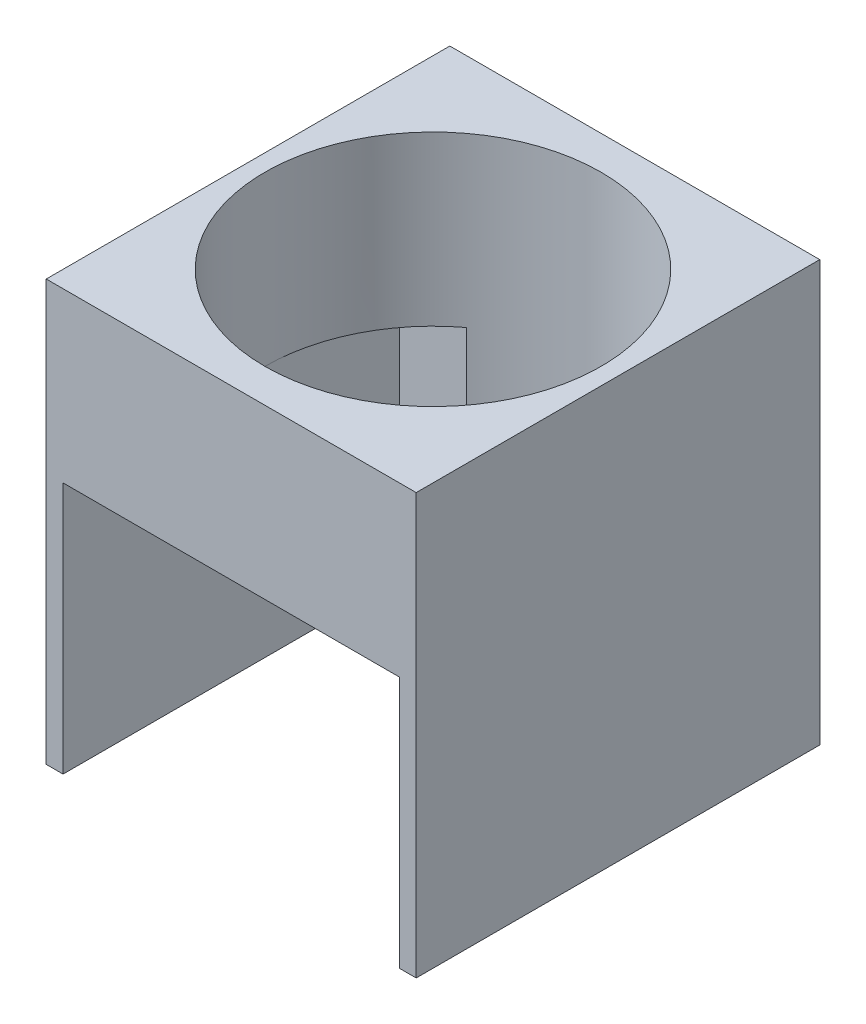
SolidWorks part; units mm, degrees
ref_plane "정면" through (0, 0, 0) normal (0, 0, 1) x (1, 0, 0)
ref_plane "윗면" through (0, 0, 0) normal (0, 1, 0) x (1, 0, 0)
ref_plane "우측면" through (0, 0, 0) normal (1, 0, 0) x (0, 0, -1)
sketch "Sketch1" plane through (0, 0, 0) normal (0, 1, 0) x (1, 0, 0)
  line L1 (0, 0) -> (670, 0)
  line L2 (0, 0) -> (0, 120)
  line L3 (0, 120) -> (670, 120)
  line L4 (670, 0) -> (670, 120)
  dimension "700" = 670
  dimension "D2" = 120
extrude "Boss-Extrude1" add sketch "Sketch1" along normal blind 530
sketch "Sketch2" plane through (0, 0, 0) normal (0, 0, 1) x (1, 0, 0)
  line L0 (0, 530) -> (0, 0) construction
  line L1 (10, 280) -> (110, 280)
  line L2 (10, 280) -> (10, 480)
  line L3 (10, 480) -> (110, 480)
  line L4 (110, 280) -> (110, 480)
  line L5 (0, 0) -> (670, 0) construction
  line L6 (120, 280) -> (120, 480)
  line L7 (120, 280) -> (220, 280)
  line L8 (220, 280) -> (220, 480)
  line L9 (120, 480) -> (220, 480)
  line L10 (230, 280) -> (230, 480)
  line L11 (230, 280) -> (330, 280)
  line L12 (330, 280) -> (330, 480)
  line L13 (230, 480) -> (330, 480)
  line L14 (340, 280) -> (340, 480)
  line L15 (340, 280) -> (440, 280)
  line L16 (440, 280) -> (440, 480)
  line L17 (340, 480) -> (440, 480)
  line L18 (450, 280) -> (450, 480)
  line L19 (450, 280) -> (550, 280)
  line L20 (550, 280) -> (550, 480)
  line L21 (450, 480) -> (550, 480)
  line L22 (560, 280) -> (560, 480)
  line L23 (560, 280) -> (660, 280)
  line L24 (660, 280) -> (660, 480)
  line L25 (560, 480) -> (660, 480)
  line L27 (10, 10) -> (660, 10)
  line L28 (10, 10) -> (10, 260)
  line L29 (10, 260) -> (660, 260)
  line L30 (660, 10) -> (660, 260)
  line L31 (0, 530) -> (670, 530) construction
  point P6 (10, 380)
  dimension "D1" = 100
  dimension "D2" = 200
  dimension "D3" = 10
  dimension "D4" = 50
  dimension "D6" = 10
  dimension "D7" = 20
  dimension "D5" = 6
extrude "Cut-Extrude1" cut sketch "Sketch2" against normal blind 100
sketch "Sketch3" plane through (0, 530, 0) normal (0, 1, 0) x (1, 0, 0)
  line L1 (670, 120) -> (0, 120) construction
  line L2 (0, 120) -> (0, 0) construction
  circle A0 centre (60, 60) radius 50
  circle A1 centre (170, 60) radius 50
  circle A2 centre (280, 60) radius 50
  circle A3 centre (390, 60) radius 50
  circle A4 centre (500, 60) radius 50
  circle A5 centre (610, 60) radius 50
  dimension "D1" = 100
  dimension "D2" = 10
  dimension "D3" = 10
  dimension "D4" = 6
extrude "Cut-Extrude2" cut sketch "Sketch3" against normal blind 260
hole_wizard "Ø12.0 (12) Diameter Hole2" positions "3DSketch1" profile "Sketch7" hole size "Ø12.0" standard "Ansi Metric"
sketch3d "3DSketch1"
  point P0 (59.7046, 270, -102.4117)
  point P2 (171.5567, 270, -102.6076)
  point P4 (280.8723, 270, -102.3969)
  point P6 (391.0687, 270, -102.7535)
  point P8 (500.7133, 270, -101.754)
  point P10 (609.5165, 270, -101.1227)
sketch "Sketch7" plane through (59.7046, 270, -102.4117) normal (1, 0, 0) x (0, 0, 1)
  line L0 (0, 0) -> (0, 33.6052)
  line L1 (0, 33.6052) -> (6, 30)
  line L2 (6, 30) -> (6, 0)
  line L5 (6, 0) -> (0, 0)
  line L10 (0, 33.6052) -> (-6, 30) construction
  line L11 (0, -6.35) -> (0, 107.95) construction
  dimension "구멍 지름" = 12
  dimension "구멍 깊이" = 30
  dimension "드릴 각도" = 118
sketch "Sketch8" plane through (0, 0, 0) normal (0, 0, 1) x (1, 0, 0)
  line L0 (660, 280) -> (660, 480) construction
  line L1 (10, 280) -> (660, 280)
  line L2 (10, 280) -> (10, 330)
  line L3 (10, 330) -> (660, 330)
  line L4 (660, 280) -> (660, 330)
  dimension "D1" = 50
extrude "Boss-Extrude2" add sketch "Sketch8" against normal blind 5
sketch "Sketch9" plane through (670, 0, 0) normal (1, 0, 0) x (0, 0, -1)
  line L0 (0, 530) -> (0, 0) construction
  line L1 (10, 10) -> (20, 10)
  line L2 (10, 10) -> (10, 260)
  line L3 (10, 260) -> (20, 260)
  line L4 (20, 10) -> (20, 260)
  line L5 (0, 0) -> (120, 0) construction
  dimension "D1" = 10
  dimension "D2" = 10
  dimension "D3" = 10
  dimension "D4" = 250
extrude "Cut-Extrude3" cut sketch "Sketch9" against normal blind 717
sketch "Sketch10" plane through (0, 10, 0) normal (0, 1, 0) x (1, 0, 0)
  line L0 (670, 120) -> (0, 120) construction
  line L1 (365, 61.9436) -> (350, 87.9243)
  line L2 (350, 87.9243) -> (320, 87.9243)
  line L3 (320, 87.9243) -> (305, 61.9436)
  line L4 (305, 61.9436) -> (320, 35.9628)
  line L5 (320, 35.9628) -> (350, 35.9628)
  line L6 (350, 35.9628) -> (365, 61.9436)
  line L7 (0, 120) -> (0, 0) construction
  circle A0 centre (335, 61.9436) radius 25.9808 construction
  dimension "D1" = 60
  dimension "D2" = 305
extrude "Cut-Extrude4" cut sketch "Sketch10" against normal blind 5
sketch "Sketch11" plane through (0, 0, -100) normal (0, 0, 1) x (1, 0, 0)
  line L0 (10, 10) -> (660, 10) construction
  line L1 (250, 10) -> (260, 10)
  line L2 (250, 10) -> (250, 110)
  line L3 (250, 110) -> (260, 110)
  line L4 (260, 10) -> (260, 110)
  line L5 (660, 10) -> (660, 260) construction
  line L6 (410, 10) -> (420, 10)
  line L7 (410, 10) -> (410, 110)
  line L8 (410, 110) -> (420, 110)
  line L9 (420, 10) -> (420, 110)
  line L10 (25, 198.4569) -> (325, 145.5588)
  line L11 (325, 145.5588) -> (325, 122.0178)
  line L12 (325, 122.0178) -> (345, 122.0178)
  line L13 (345, 122.0178) -> (345, 145.5588)
  line L14 (345, 145.5588) -> (645, 198.4569)
  line L15 (645, 198.4569) -> (25, 198.4569)
  point P18 (345, 133.7883)
  dimension "D1" = 10
  dimension "D2" = 10
  dimension "D3" = 100
  dimension "D4" = 100
  dimension "D5" = 150
  dimension "D6" = 240
  dimension "D7" = 20
  dimension "D8" = 65
  dimension "D9" = 100
  dimension "D10" = 620
  dimension "D11" = 100
extrude "Boss-Extrude3" add sketch "Sketch11" along normal blind 78 separate body
sketch "Sketch12" plane through (0, 0, -100) normal (0, 0, 1) x (1, 0, 0)
  line L0 (660, 260) -> (10, 260) construction
  line L1 (75.1986, 260) -> (95.1986, 260)
  line L2 (75.1986, 260) -> (75.1986, 230)
  line L3 (75.1986, 230) -> (95.1986, 230)
  line L4 (95.1986, 260) -> (95.1986, 230)
  line L5 (65.1986, 260) -> (65.1986, 240) construction
  line L6 (185.1986, 260) -> (185.1986, 230)
  line L7 (185.1986, 260) -> (205.1986, 260)
  line L8 (205.1986, 260) -> (205.1986, 230)
  line L9 (185.1986, 230) -> (205.1986, 230)
  line L10 (295.1986, 260) -> (295.1986, 230)
  line L11 (295.1986, 260) -> (315.1986, 260)
  line L12 (315.1986, 260) -> (315.1986, 230)
  line L13 (295.1986, 230) -> (315.1986, 230)
  line L14 (405.1986, 260) -> (405.1986, 230)
  line L15 (405.1986, 260) -> (425.1986, 260)
  line L16 (425.1986, 260) -> (425.1986, 230)
  line L17 (405.1986, 230) -> (425.1986, 230)
  line L18 (515.1986, 260) -> (515.1986, 230)
  line L19 (515.1986, 260) -> (535.1986, 260)
  line L20 (535.1986, 260) -> (535.1986, 230)
  line L21 (515.1986, 230) -> (535.1986, 230)
  line L22 (625.1986, 260) -> (625.1986, 230)
  line L23 (625.1986, 260) -> (645.1986, 260)
  line L24 (645.1986, 260) -> (645.1986, 230)
  line L25 (625.1986, 230) -> (645.1986, 230)
  dimension "D1" = 20
  dimension "D2" = 30
  dimension "D3" = 10
  dimension "D4" = 6
extrude "Cut-Extrude5" cut sketch "Sketch12" against normal blind 80
sketch "Sketch15" plane through (345, 0, 0) normal (1, 0, 0) x (0, 0, -1)
  line L0 (20, 10) -> (20, 260) construction
  line L1 (20, 121.4638) -> (50, 121.4638)
  line L2 (20, 121.4638) -> (20, 145)
  line L3 (20, 145) -> (50, 145)
  line L4 (50, 121.4638) -> (50, 145)
  line L5 (120, 530) -> (120, 0) construction
  line L6 (100, 116.0134) -> (70, 116.0134)
  line L7 (100, 116.0134) -> (100, 145)
  line L8 (100, 145) -> (70, 145)
  line L9 (70, 116.0134) -> (70, 145)
  line L10 (20, 260) -> (10, 260) construction
  dimension "D1" = 20
  dimension "D2" = 20
  dimension "D3" = 115
  dimension "D4" = 30
extrude "Cut-Extrude7" cut sketch "Sketch15" against normal blind 35
shell "Shell1" thickness 3
sketch "Sketch16" plane through (0, 122.0178, 0) normal (0, -1, 0) x (1, 0, 0)
  line L0 (345, -50) -> (325, -50) construction
  line L1 (328, -53) -> (342, -53)
  line L2 (328, -53) -> (328, -67)
  line L3 (328, -67) -> (342, -67)
  line L4 (342, -53) -> (342, -67)
  line L5 (325, -50) -> (325, -70) construction
  line L6 (345, -50) -> (345, -70) construction
  line L7 (325, -70) -> (345, -70) construction
  dimension "D1" = 3
  dimension "D2" = 3
  dimension "D3" = 3
  dimension "D4" = 3
extrude "Cut-Extrude8" cut sketch "Sketch16" against normal blind 35
sketch "Sketch17" plane through (0, 0, 0) normal (0, 0, 1) x (1, 0, 0)
  text T0 "<b>DIFF_USER</b>" font "Britannic Bold" height in points 72
extrude "Boss-Extrude4" add sketch "Sketch17" along normal blind 5
sketch "Sketch18" plane through (0, 0, 0) normal (0, 0, 1) x (1, 0, 0)
  line L0 (670, 530) -> (670, 0) construction
  line L1 (0, 0) -> (670, 0)
  line L2 (0, 0) -> (0, 280)
  line L3 (0, 280) -> (670, 280)
  line L4 (670, 0) -> (670, 280)
  dimension "D1" = 280
extrude "Cut-Extrude10" cut sketch "Sketch18" against normal blind 159
sketch "Sketch19" plane through (0, 0, 0) normal (0, 0, 1) x (1, 0, 0)
  line L0 (0, 530) -> (670, 530) construction
  line L1 (670, 280) -> (555, 280)
  line L2 (670, 280) -> (670, 530)
  line L3 (670, 530) -> (555, 530)
  line L4 (555, 280) -> (555, 530)
  line L5 (670, 280) -> (0, 280) construction
  line L6 (0, 530) -> (445, 530)
  line L7 (0, 530) -> (0, 280)
  line L8 (0, 280) -> (445, 280)
  line L9 (445, 530) -> (445, 280)
  dimension "D1" = 115
  dimension "D2" = 110
extrude "Cut-Extrude11" cut sketch "Sketch19" against normal through all both and the other way through all
sketch "Sketch20" plane through (0, 0, 0) normal (0, 0, 1) x (1, 0, 0)
  line L0 (555, 307.2638) -> (555, 530) construction
  line L1 (445, 280) -> (555, 280)
  line L2 (445, 280) -> (445, 405)
  line L3 (445, 405) -> (555, 405)
  line L4 (555, 280) -> (555, 405)
  dimension "D1" = 125
extrude "Cut-Extrude12" cut sketch "Sketch20" against normal through all both and the other way through all
